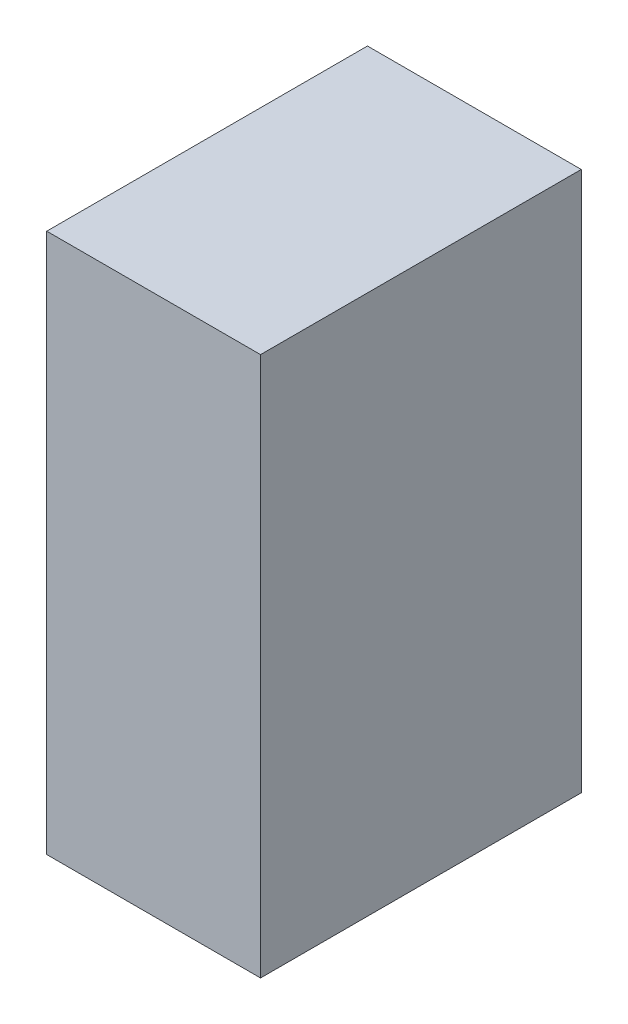
SolidWorks part; units mm, degrees
ref_plane "Front Plane" through (0, 0, 0) normal (0, 0, 1) x (1, 0, 0)
ref_plane "Top Plane" through (0, 0, 0) normal (0, 1, 0) x (1, 0, 0)
ref_plane "Right Plane" through (0, 0, 0) normal (1, 0, 0) x (0, 0, -1)
sketch "Sketch2" plane through (0, 0, 0) normal (0, 0, 1) x (1, 0, 0)
  line L5 (-10, -25.25) -> (10, -25.25)
  line L6 (-10, -25.25) -> (-10, 25.25)
  line L7 (-10, 25.25) -> (10, 25.25)
  line L8 (10, -25.25) -> (10, 25.25)
  line L9 (-10, -25.25) -> (-9, -22.725) construction
  line L10 (-10, 25.25) -> (-9, 22.725) construction
  line L11 (9, -24.25) -> (9, -22.725)
  line L13 (-9, -24.25) -> (-9, -22.725)
  line L14 (-9, 22.725) -> (-9, 24.25)
  line L15 (-9, -24.25) -> (-9, 24.25) construction
  line L16 (9, 22.725) -> (10, 25.25) construction
  line L17 (9, -22.725) -> (10, -25.25) construction
  line L18 (-9, 24.25) -> (9, 24.25) construction
  line L19 (9, 22.725) -> (9, 24.25)
  line L20 (9, -24.25) -> (9, 24.25) construction
  line L21 (-9, -24.25) -> (9, -24.25) construction
  point P0 (0, 0)
  dimension "D1" = 20
  dimension "D2" = 50.5
  dimension "D3" = 1
extrude "Boss-Extrude1" add sketch "Sketch2" along normal blind 30
shell "Shell1" thickness 2
sketch "Sketch4" plane through (0, -25.25, 0) normal (0, -1, 0) x (1, 0, 0)
  text T0 "ACID"
extrude "Cut-Extrude1" cut sketch "Sketch4" against normal blind 0.001
